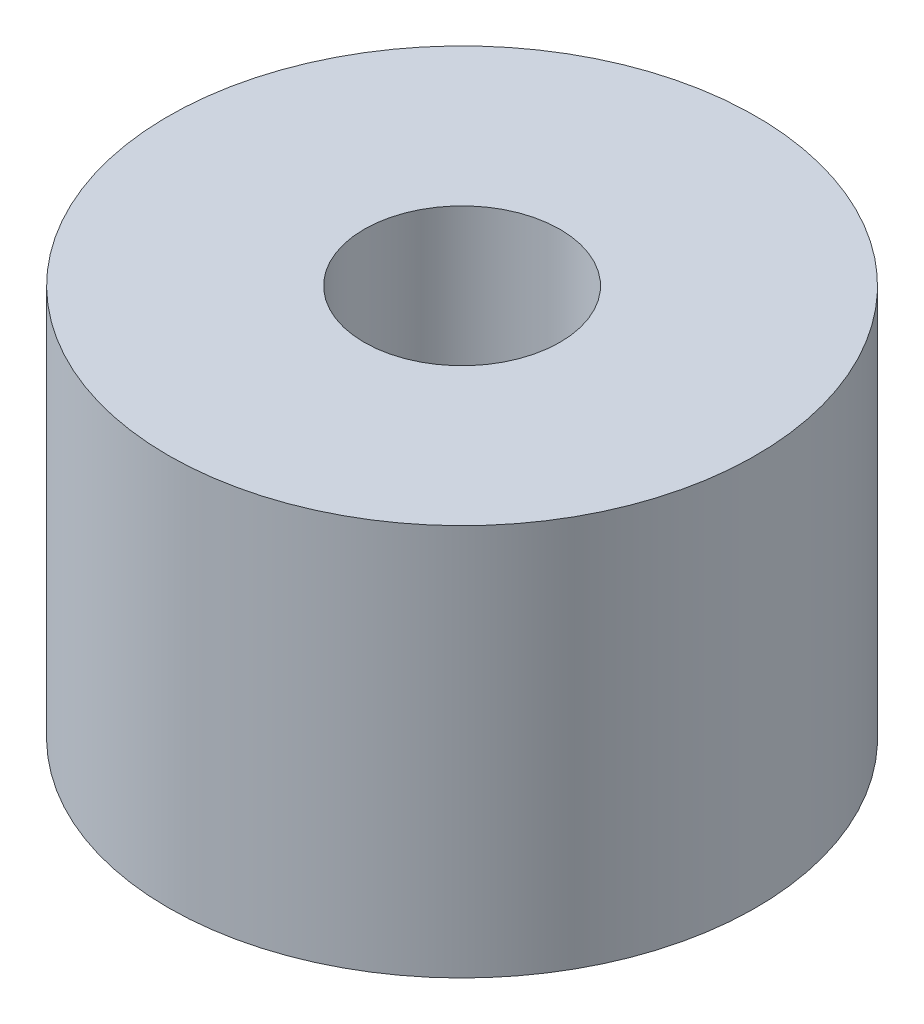
SolidWorks part; units mm, degrees
ref_plane "Front Plane" through (0, 0, 0) normal (0, 0, 1) x (1, 0, 0)
ref_plane "Top Plane" through (0, 0, 0) normal (0, 1, 0) x (1, 0, 0)
ref_plane "Right Plane" through (0, 0, 0) normal (1, 0, 0) x (0, 0, -1)
sketch "Sketch1" plane through (0, 0, 0) normal (0, 1, 0) x (1, 0, 0)
  circle A0 centre (0, 0) radius 3.75
  circle A1 centre (0, 0) radius 1.25
  dimension "D1" = 7.5
  dimension "D2" = 2.5
extrude "Boss-Extrude1" add sketch "Sketch1" along normal blind 5
